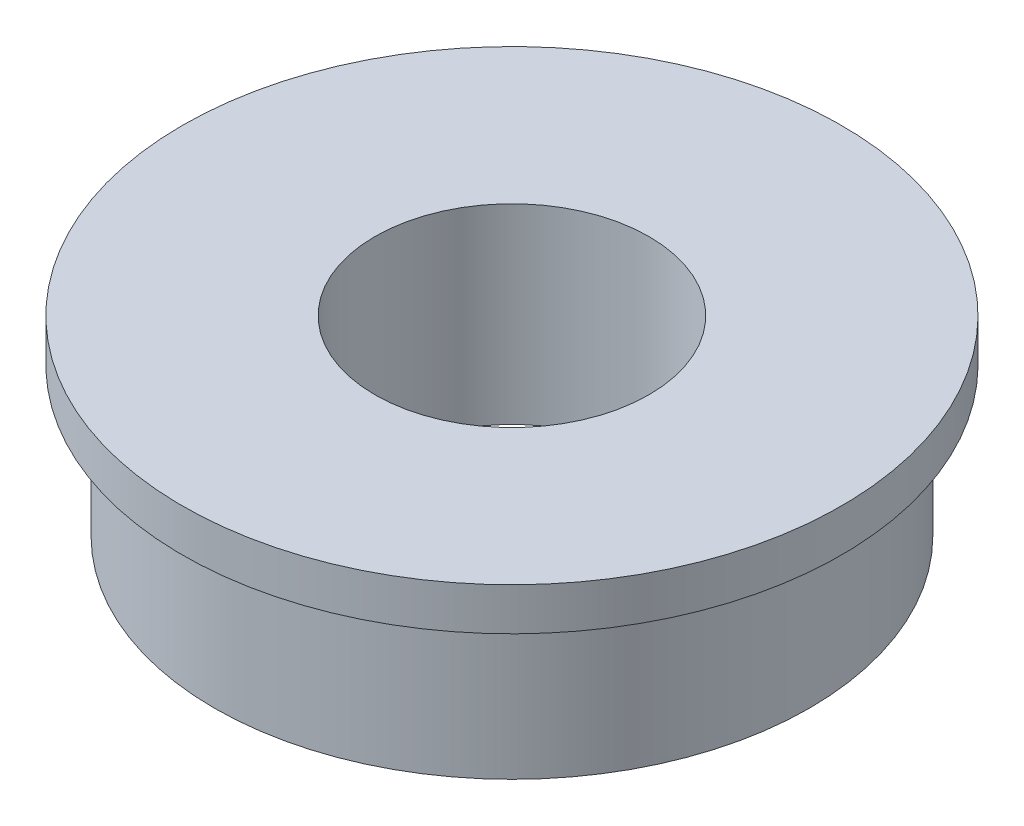
SolidWorks part; units mm, degrees
ref_plane "Alzado" through (0, 0, 0) normal (0, 0, 1) x (1, 0, 0)
ref_plane "Planta" through (0, 0, 0) normal (0, 1, 0) x (1, 0, 0)
ref_plane "Vista lateral" through (0, 0, 0) normal (1, 0, 0) x (0, 0, -1)
sketch "Croquis2" plane through (0, 0, 0) normal (0, 0, 1) x (1, 0, 0)
  line L0 (0, 3.5687) -> (0, -3.5687) construction
  line L1 (0, 3.5687) -> (0, -3.5687)
  line L6 (0, 3.5687) -> (-12.3063, 3.5687)
  line L7 (-12.3063, 3.5687) -> (-12.3063, 1.9812)
  line L8 (-12.3063, 1.9812) -> (-11.1125, 1.9812)
  line L9 (-11.1125, 1.9812) -> (-11.1125, -3.5687)
  line L10 (-11.1125, -3.5687) -> (0, -3.5687)
  point P3 (0, 0)
  dimension "FlangeWidth" = 1.5875
  dimension "OverallWidth" = 7.1374
  dimension "OuterDiameter " = 22.225
  dimension "OuterFlangeDiameter" = 24.6126
revolve "Revolución1" add sketch "Croquis2" angle 360 about L0
sketch "Croquis3" plane through (0, 0, 0) normal (0, 1, 0) x (1, 0, 0)
  circle A0 centre (0, 0) radius 5.1181
  dimension "InnerDiameter" = 10.2362
extrude "Round Corte" cut sketch "Croquis3" against normal through all both and the other way through all
sketch "Croquis4" plane through (0, 0, 0) normal (0, 1, 0) x (1, 0, 0)
  line L1 (2.9549, -5.1181) -> (5.9099, 0)
  line L2 (5.9099, 0) -> (2.9549, 5.1181)
  line L3 (2.9549, 5.1181) -> (-2.9549, 5.1181)
  line L4 (-2.9549, 5.1181) -> (-5.9099, 0)
  line L5 (-5.9099, 0) -> (-2.9549, -5.1181)
  line L6 (-2.9549, -5.1181) -> (2.9549, -5.1181)
  circle A0 centre (0, 0) radius 5.1181 construction
  circle A1 centre (0, 0) radius 5.1181 construction
extrude "Cortar-Extruir2" [suppressed] cut sketch "Croquis4" against normal through all both and the other way through all
other "PropertyManager" [suppressed]
